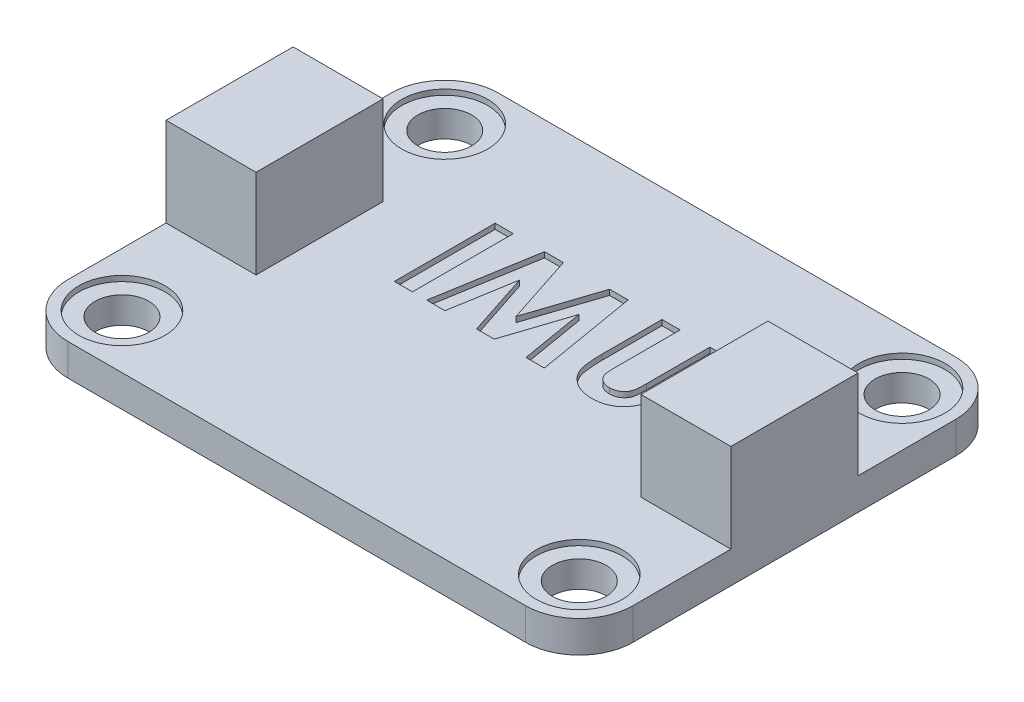
SolidWorks part; units mm, degrees
ref_plane "Front Plane" through (0, 0, 0) normal (0, 0, 1) x (1, 0, 0)
ref_plane "Top Plane" through (0, 0, 0) normal (0, 1, 0) x (1, 0, 0)
ref_plane "Right Plane" through (0, 0, 0) normal (1, 0, 0) x (0, 0, -1)
sketch "Sketch1" plane through (0, 0, 0) normal (0, 1, 0) x (1, 0, 0)
  line L1 (-13.335, -10.16) -> (13.335, -10.16)
  line L2 (-13.335, -10.16) -> (-13.335, 10.16)
  line L3 (-13.335, 10.16) -> (13.335, 10.16)
  line L4 (13.335, -10.16) -> (13.335, 10.16)
  line L5 (-13.335, -10.16) -> (13.335, 10.16) construction
  line L6 (-13.335, 10.16) -> (13.335, -10.16) construction
  point P0 (0, 0)
  dimension "D1" = 20.32
  dimension "D2" = 26.67
extrude "Boss-Extrude1" add sketch "Sketch1" along normal blind 1.5
sketch "Sketch2" plane through (0, 1.5, 0) normal (0, 1, 0) x (1, 0, 0)
  line L1 (-10.795, -7.62) -> (10.795, -7.62) construction
  line L2 (-10.795, -7.62) -> (-10.795, 7.62) construction
  line L3 (-10.795, 7.62) -> (10.795, 7.62) construction
  line L4 (10.795, -7.62) -> (10.795, 7.62) construction
  line L5 (-10.795, -7.62) -> (10.795, 7.62) construction
  line L6 (-10.795, 7.62) -> (10.795, -7.62) construction
  circle A0 centre (10.795, 7.62) radius 1.27
  circle A1 centre (-10.795, 7.62) radius 1.27
  circle A2 centre (-10.795, -7.62) radius 1.27
  circle A3 centre (10.795, -7.62) radius 1.27
  point P0 (0, 0)
  dimension "D3" = 2.54
  dimension "D1" = 21.59
  dimension "D2" = 15.24
extrude "Cut-Extrude1" cut sketch "Sketch2" against normal through all
fillet "Fillet1" radius 2.54 4 edges at (-13.335, 0.75, -10.16) (13.335, 0.75, -10.16) (13.335, 0.75, 10.16) (-13.335, 0.75, 10.16)
sketch "Sketch3" plane through (0, 1.5, 0) normal (0, 1, 0) x (1, 0, 0)
  line L0 (-13.335, 0) -> (13.335, 0) construction
  line L1 (13.335, -7.62) -> (13.335, 7.62) construction
  text T0 "<b>IMU</b>" font "Century Gothic" height in points 18
  point P6 (0, 0)
extrude "Cut-Extrude2" cut sketch "Sketch3" against normal blind 0.254
sketch "Sketch4" plane through (0, 1.5, 0) normal (0, 1, 0) x (1, 0, 0)
  circle A0 centre (-10.795, 7.62) radius 2.032
  circle A1 centre (10.795, 7.62) radius 2.032
  circle A2 centre (10.795, -7.62) radius 2.032
  circle A3 centre (-10.795, -7.62) radius 2.032
  circle A4 centre (-10.795, -7.62) radius 1.27 construction
  circle A5 centre (10.795, -7.62) radius 1.27 construction
  circle A6 centre (10.795, 7.62) radius 1.27 construction
  circle A7 centre (-10.795, 7.62) radius 1.27 construction
  circle A8 centre (-10.795, -7.62) radius 1.27
  circle A9 centre (10.795, -7.62) radius 1.27
  circle A10 centre (10.795, 7.62) radius 1.27
  circle A11 centre (-10.795, 7.62) radius 1.27
  dimension "D1" = 4.064
extrude "Cut-Extrude3" cut sketch "Sketch4" against normal blind 0.254
sketch "Sketch5" plane through (0, 1.5, 0) normal (0, 1, 0) x (1, 0, 0)
  line L0 (-13.335, 0) -> (49986.665, 0) construction
  line L1 (-13.335, 7.62) -> (-13.335, -7.62) construction
  line L2 (13.335, -7.62) -> (13.335, 7.62) construction
  line L3 (-9.085, -3) -> (-13.335, -3)
  line L4 (-9.085, -3) -> (-9.085, 3)
  line L5 (-9.085, 3) -> (-13.335, 3)
  line L6 (-13.335, -3) -> (-13.335, 3)
  line L7 (-9.085, -3) -> (-13.335, 3) construction
  line L8 (-9.085, 3) -> (-13.335, -3) construction
  line L9 (9.085, -3) -> (13.335, -3)
  line L10 (9.085, -3) -> (9.085, 3)
  line L11 (9.085, 3) -> (13.335, 3)
  line L12 (13.335, -3) -> (13.335, 3)
  line L13 (9.085, -3) -> (13.335, 3) construction
  line L14 (9.085, 3) -> (13.335, -3) construction
  point P4 (-13.335, 0)
  point P5 (-11.21, 0)
  point P10 (11.21, 0)
  dimension "D1" = 6
  dimension "D2" = 4.25
extrude "Boss-Extrude3" add sketch "Sketch5" along normal blind 4.2
